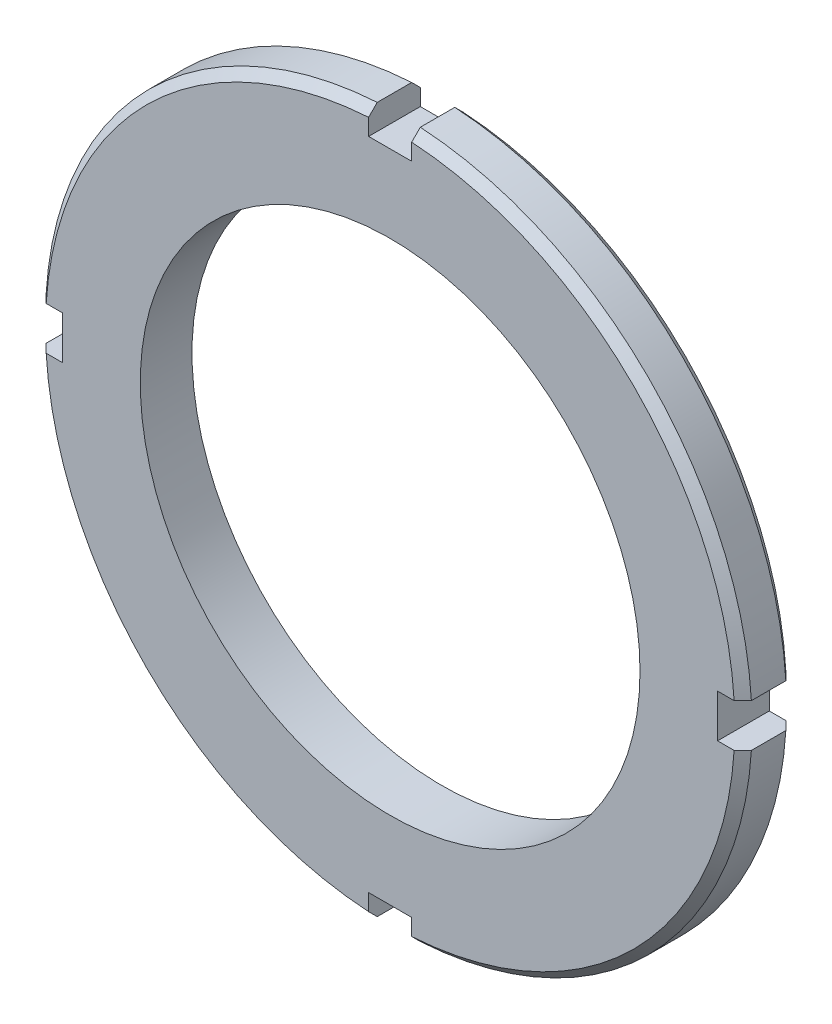
SolidWorks part; units mm, degrees
ref_plane "前视基准面" through (0, 0, 0) normal (0, 0, 1) x (1, 0, 0)
ref_plane "上视基准面" through (0, 0, 0) normal (0, 1, 0) x (1, 0, 0)
ref_plane "右视基准面" through (0, 0, 0) normal (1, 0, 0) x (0, 0, -1)
sketch "草图1" plane through (0, 0, 0) normal (0, 0, 1) x (1, 0, 0)
  circle A0 centre (0, 0) radius 41
  dimension "D1" = 82
extrude "凸台-拉伸1" add sketch "草图1" along normal blind 6
hole_wizard "M64 螺纹孔1" positions "草图2" profile "草图4" tap size "M64" standard "GB" end condition through all
sketch "草图2" plane through (0, 0, 6) normal (0, 0, 1) x (1, 0, 0)
  point P0 (0, 0)
sketch "草图4" plane through (0, 0, 6) normal (1, 0, 0) x (0, -1, 0)
  line L0 (0, 0) -> (0, 6)
  line L1 (0, 6) -> (29, 6)
  line L2 (29, 6) -> (29, 0)
  line L5 (29, 0) -> (0, 0)
  line L11 (0, -6.35) -> (0, 107.95) construction
  dimension "通孔螺纹孔钻头直径" = 58
  dimension "通孔螺纹孔钻头深度" = 6
cosmetic thread "孔螺纹线1" parameters "D2"=64
chamfer "倒角1" distance 1 angle 45 2 edges at (41, 0, 0) (41, 0, 6)
sketch "草图5" plane through (0, 0, 6) normal (0, 0, 1) x (1, 0, 0)
  line L0 (3.3, 0) -> (-3.3, 0) construction
  line L1 (38, -2.5) -> (41, -2.5)
  line L2 (38, -2.5) -> (38, 2.5)
  line L3 (38, 2.5) -> (41, 2.5)
  line L4 (41, -2.5) -> (41, 2.5)
  line L5 (38, -2.5) -> (41, 2.5) construction
  line L6 (38, 2.5) -> (41, -2.5) construction
  circle A0 centre (0, 0) radius 41 construction
  point P0 (39.5, 0)
  dimension "D1" = 5
  dimension "D2" = 3
extrude "切除-拉伸1" cut sketch "草图5" against normal through all
pattern_circular "阵列(圆周)1" count 4 over 360 about axis through (0, 0, 0) along (0, 0, 1) of "切除-拉伸1"
